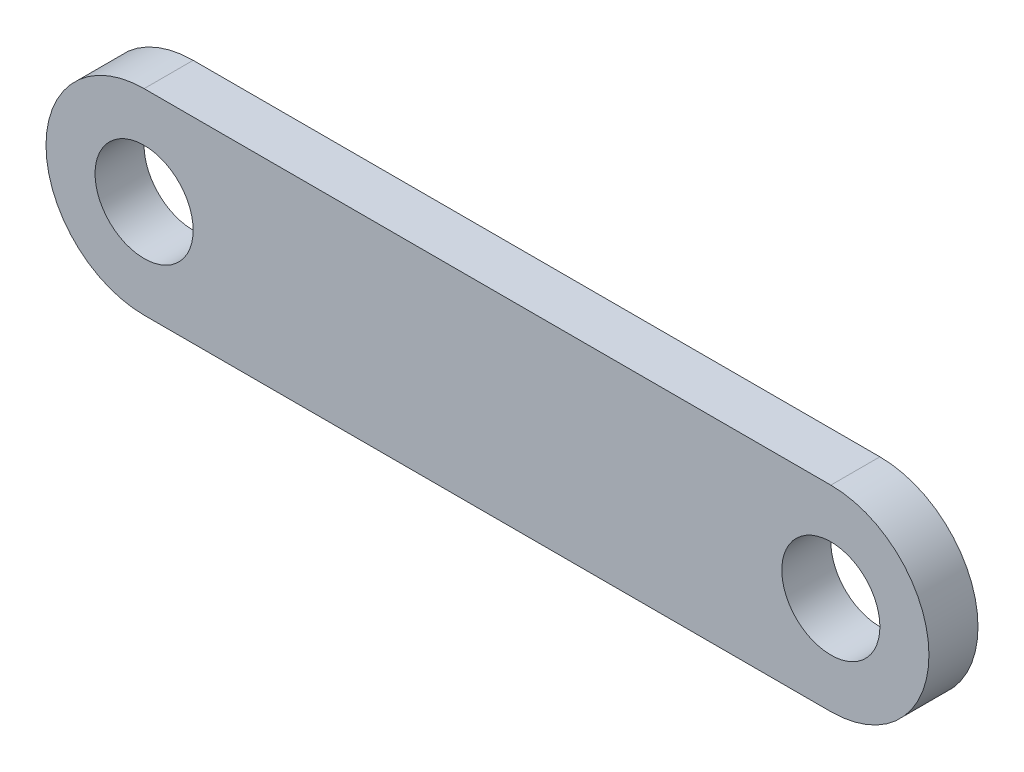
SolidWorks part; units mm, degrees
ref_plane "Front Plane" through (0, 0, 0) normal (0, 0, 1) x (1, 0, 0)
ref_plane "Top Plane" through (0, 0, 0) normal (0, 1, 0) x (1, 0, 0)
ref_plane "Right Plane" through (0, 0, 0) normal (1, 0, 0) x (0, 0, -1)
sketch "Sketch1" plane through (0, 0, 0) normal (0, 0, 1) x (1, 0, 0)
  line L0 (-54.9335, 27.5548) -> (15.0665, 27.5548)
  line L1 (-54.9335, 7.5548) -> (15.0665, 7.5548)
  arc A0 (-54.9335, 27.5548) -> (-54.9335, 7.5548) centre (-54.9335, 17.5548) ccw
  arc A1 (15.0665, 7.5548) -> (15.0665, 27.5548) centre (15.0665, 17.5548) ccw
  circle A2 centre (-54.9335, 17.5548) radius 5
  circle A3 centre (15.0665, 17.5548) radius 5
  dimension "D1" = 20
  dimension "D2" = 20
  dimension "D4" = 10
  dimension "D5" = 10
  dimension "D3" = 70
extrude "Boss-Extrude1" add sketch "Sketch1" along normal blind 5
